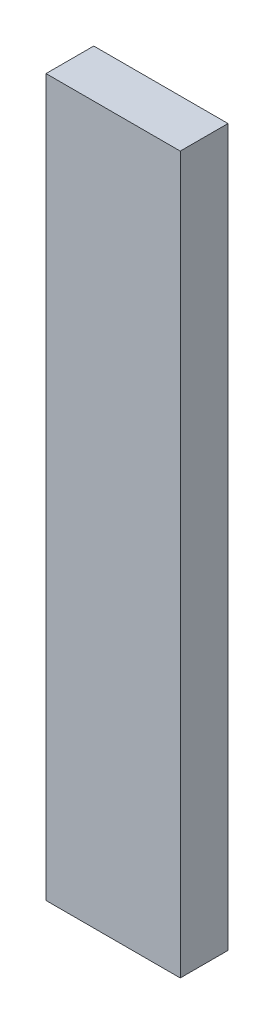
SolidWorks part; units mm, degrees
ref_plane "Front Plane" through (0, 0, 0) normal (0, 0, 1) x (1, 0, 0)
ref_plane "Top Plane" through (0, 0, 0) normal (0, 1, 0) x (1, 0, 0)
ref_plane "Right Plane" through (0, 0, 0) normal (1, 0, 0) x (0, 0, -1)
sketch "Sketch1" plane through (0, 0, 0) normal (0, 0, 1) x (1, 0, 0)
  line L1 (-11.248, 60) -> (11.248, 60)
  line L2 (-11.248, 60) -> (-11.248, -60)
  line L3 (-11.248, -60) -> (11.248, -60)
  line L4 (11.248, 60) -> (11.248, -60)
  line L5 (-11.248, 60) -> (11.248, -60) construction
  line L6 (-11.248, -60) -> (11.248, 60) construction
  point P0 (0, 0)
  dimension "D1" = 120
  dimension "D2" = 22.496
extrude "Boss-Extrude1" add sketch "Sketch1" along normal blind 8
